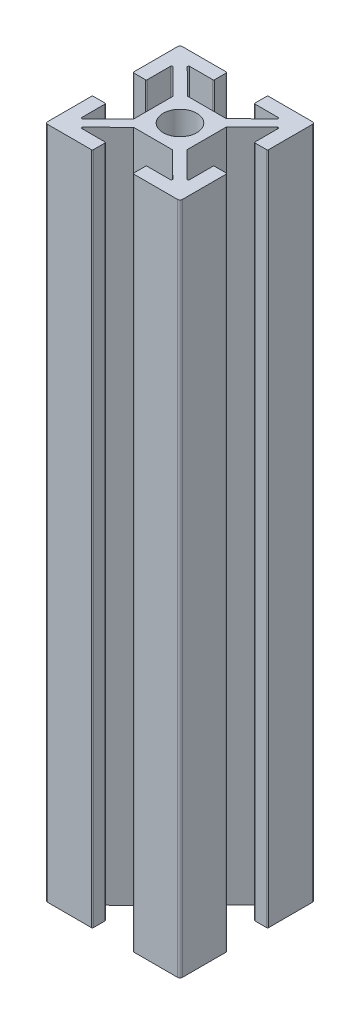
SolidWorks part; units mm, degrees
ref_plane "Front Plane" through (0, 0, 0) normal (0, 0, 1) x (1, 0, 0)
ref_plane "Top Plane" through (0, 0, 0) normal (0, 1, 0) x (1, 0, 0)
ref_plane "Right Plane" through (0, 0, 0) normal (1, 0, 0) x (0, 0, -1)
sketch "Sketch1" plane through (0, 0, 0) normal (0, 1, 0) x (1, 0, 0)
  line L0 (-5.3577, -5.6795) -> (-3.6577, -5.6795)
  line L1 (1.3423, 1.3205) -> (-5.1577, 1.3205)
  line L2 (-5.5077, -5.5295) -> (-5.5077, 0.9705)
  line L3 (7.3792, -4.6795) -> (1.6054, -4.6795)
  line L4 (0.5386, -11.6249) -> (0.5386, -5.7341)
  line L5 (-3.5077, -5.5295) -> (-3.5077, -2.0933)
  line L6 (-2.0758, -0.6795) -> (1.3423, -0.6795)
  line L7 (1.4923, -0.5295) -> (1.4923, 1.1705)
  line L8 (-3.5077, -0.6795) -> (0.5386, -4.6795) construction
  line L9 (-3.2523, -1.9866) -> (0.5386, -5.7341)
  line L10 (-2.1813, -0.9362) -> (1.6054, -4.6795)
  line L11 (12.4923, -0.6795) -> (8.446, -4.6795) construction
  line L12 (4.4923, -8.6795) -> (4.4923, 3.0091) construction
  line L13 (4.4923, -8.6795) -> (-10.4455, -8.6795) construction
  line L14 (11.1658, -0.9362) -> (7.3792, -4.6795)
  line L15 (12.2368, -1.9866) -> (8.446, -5.7341)
  line L16 (7.4923, -0.5295) -> (7.4923, 1.1705)
  line L17 (11.0604, -0.6795) -> (7.6423, -0.6795)
  line L18 (12.4923, -5.5295) -> (12.4923, -2.0933)
  line L19 (8.446, -11.6249) -> (8.446, -5.7341)
  line L20 (14.4923, -5.5295) -> (14.4923, 0.9705)
  line L21 (7.6423, 1.3205) -> (14.1423, 1.3205)
  line L22 (14.3423, -5.6795) -> (12.6423, -5.6795)
  line L23 (12.4923, -16.6795) -> (8.446, -12.6795) construction
  line L24 (-3.5077, -16.6795) -> (0.5386, -12.6795) construction
  line L25 (14.3423, -11.6795) -> (12.6423, -11.6795)
  line L26 (7.6423, -18.6795) -> (14.1423, -18.6795)
  line L27 (14.4923, -11.8295) -> (14.4923, -18.3295)
  line L28 (12.4923, -11.8295) -> (12.4923, -15.2657)
  line L29 (11.0604, -16.6795) -> (7.6423, -16.6795)
  line L30 (7.4923, -16.8295) -> (7.4923, -18.5295)
  line L31 (12.2368, -15.3723) -> (8.446, -11.6249)
  line L32 (11.1658, -16.4228) -> (7.3792, -12.6795)
  line L33 (-2.1813, -16.4228) -> (1.6054, -12.6795)
  line L34 (-3.2523, -15.3723) -> (0.5386, -11.6249)
  line L35 (1.4923, -16.8295) -> (1.4923, -18.5295)
  line L36 (-2.0758, -16.6795) -> (1.3423, -16.6795)
  line L37 (-3.5077, -11.8295) -> (-3.5077, -15.2657)
  line L38 (7.3792, -12.6795) -> (1.6054, -12.6795)
  line L39 (-5.5077, -11.8295) -> (-5.5077, -18.3295)
  line L40 (1.3423, -18.6795) -> (-5.1577, -18.6795)
  line L41 (-5.3577, -11.6795) -> (-3.6577, -11.6795)
  circle A0 centre (4.4923, -8.6795) radius 2.5
  arc A1 (-5.5077, 0.9705) -> (-5.1577, 1.3205) centre (-5.1577, 0.9705) cw
  arc A2 (-5.3577, -5.6795) -> (-5.5077, -5.5295) centre (-5.3577, -5.5295) cw
  arc A3 (-3.6577, -5.6795) -> (-3.5077, -5.5295) centre (-3.6577, -5.5295) ccw
  arc A4 (1.3423, 1.3205) -> (1.4923, 1.1705) centre (1.3423, 1.1705) cw
  arc A5 (1.3423, -0.6795) -> (1.4923, -0.5295) centre (1.3423, -0.5295) ccw
  arc A6 (-2.1813, -0.9362) -> (-2.0758, -0.6795) centre (-2.0758, -0.8295) cw
  arc A7 (-3.2523, -1.9866) -> (-3.5077, -2.0933) centre (-3.3577, -2.0933) ccw
  arc A8 (12.2368, -1.9866) -> (12.4923, -2.0933) centre (12.3423, -2.0933) cw
  arc A9 (11.1658, -0.9362) -> (11.0604, -0.6795) centre (11.0604, -0.8295) ccw
  arc A10 (7.6423, -0.6795) -> (7.4923, -0.5295) centre (7.6423, -0.5295) cw
  arc A11 (7.6423, 1.3205) -> (7.4923, 1.1705) centre (7.6423, 1.1705) ccw
  arc A12 (12.6423, -5.6795) -> (12.4923, -5.5295) centre (12.6423, -5.5295) cw
  arc A13 (14.3423, -5.6795) -> (14.4923, -5.5295) centre (14.3423, -5.5295) ccw
  arc A14 (14.4923, 0.9705) -> (14.1423, 1.3205) centre (14.1423, 0.9705) ccw
  arc A15 (14.4923, -18.3295) -> (14.1423, -18.6795) centre (14.1423, -18.3295) cw
  arc A16 (14.3423, -11.6795) -> (14.4923, -11.8295) centre (14.3423, -11.8295) cw
  arc A17 (12.6423, -11.6795) -> (12.4923, -11.8295) centre (12.6423, -11.8295) ccw
  arc A18 (7.6423, -18.6795) -> (7.4923, -18.5295) centre (7.6423, -18.5295) cw
  arc A19 (7.6423, -16.6795) -> (7.4923, -16.8295) centre (7.6423, -16.8295) ccw
  arc A20 (11.1658, -16.4228) -> (11.0604, -16.6795) centre (11.0604, -16.5295) cw
  arc A21 (12.2368, -15.3723) -> (12.4923, -15.2657) centre (12.3423, -15.2657) ccw
  arc A22 (-3.2523, -15.3723) -> (-3.5077, -15.2657) centre (-3.3577, -15.2657) cw
  arc A23 (-2.1813, -16.4228) -> (-2.0758, -16.6795) centre (-2.0758, -16.5295) ccw
  arc A24 (1.3423, -16.6795) -> (1.4923, -16.8295) centre (1.3423, -16.8295) cw
  arc A25 (1.3423, -18.6795) -> (1.4923, -18.5295) centre (1.3423, -18.5295) ccw
  arc A26 (-3.6577, -11.6795) -> (-3.5077, -11.8295) centre (-3.6577, -11.8295) cw
  arc A27 (-5.3577, -11.6795) -> (-5.5077, -11.8295) centre (-5.3577, -11.8295) ccw
  arc A28 (-5.5077, -18.3295) -> (-5.1577, -18.6795) centre (-5.1577, -18.3295) ccw
  point P27 (7.5849, -0.6795)
  point P28 (14.5849, -18.6795)
  point P47 (8.446, -8.6795)
  point P57 (4.4923, -4.6795)
  point P59 (7.5849, 1.3205)
  point P60 (12.5849, -5.6795)
  point P61 (14.5849, -5.6795)
  point P62 (14.5849, 1.3205)
  point P112 (0.5386, -8.6795)
  point P113 (14.5849, -11.6795)
  point P114 (12.5849, -11.6795)
  point P115 (7.5849, -18.6795)
  point P116 (4.4923, -12.6795)
  point P117 (1.4923, -16.6795)
  point P118 (1.4923, -18.6795)
  point P119 (-3.5077, -11.6795)
  point P120 (7.5849, -16.6795)
  point P121 (-5.5077, -11.6795)
  point P122 (-5.5077, -18.6795)
  dimension "D3" = 0.35
  dimension "D4" = 0.15
  dimension "D5" = 0.15
  dimension "D6" = 0.15
  dimension "D7" = 0.15
  dimension "D8" = 0.15
  dimension "D9" = 0.15
  dimension "D1" = 0.75
  dimension "D2" = 0.75
  dimension "D10" = 20
  dimension "D11" = 20
extrude "Boss-Extrude1" add sketch "Sketch1" along normal blind 100
sketch "Sketch2" plane through (0, 0, 12.6795) normal (0, 0, 1) x (1, 0, 0)
  line L0 (4.4923, 100) -> (4.4923, 0) construction
  line L1 (1.6054, 100) -> (7.3792, 100) construction
  line L2 (1.6054, 0) -> (7.3792, 0) construction
  circle A4 centre (4.4923, 53.4184) radius 2.5
  circle A5 centre (4.4923, 93.4184) radius 2.5
  dimension "D2" = 5
  dimension "D3" = 40
  dimension "D4" = 5
extrude "Cut-Extrude1" cut sketch "Sketch2" against normal blind 1
